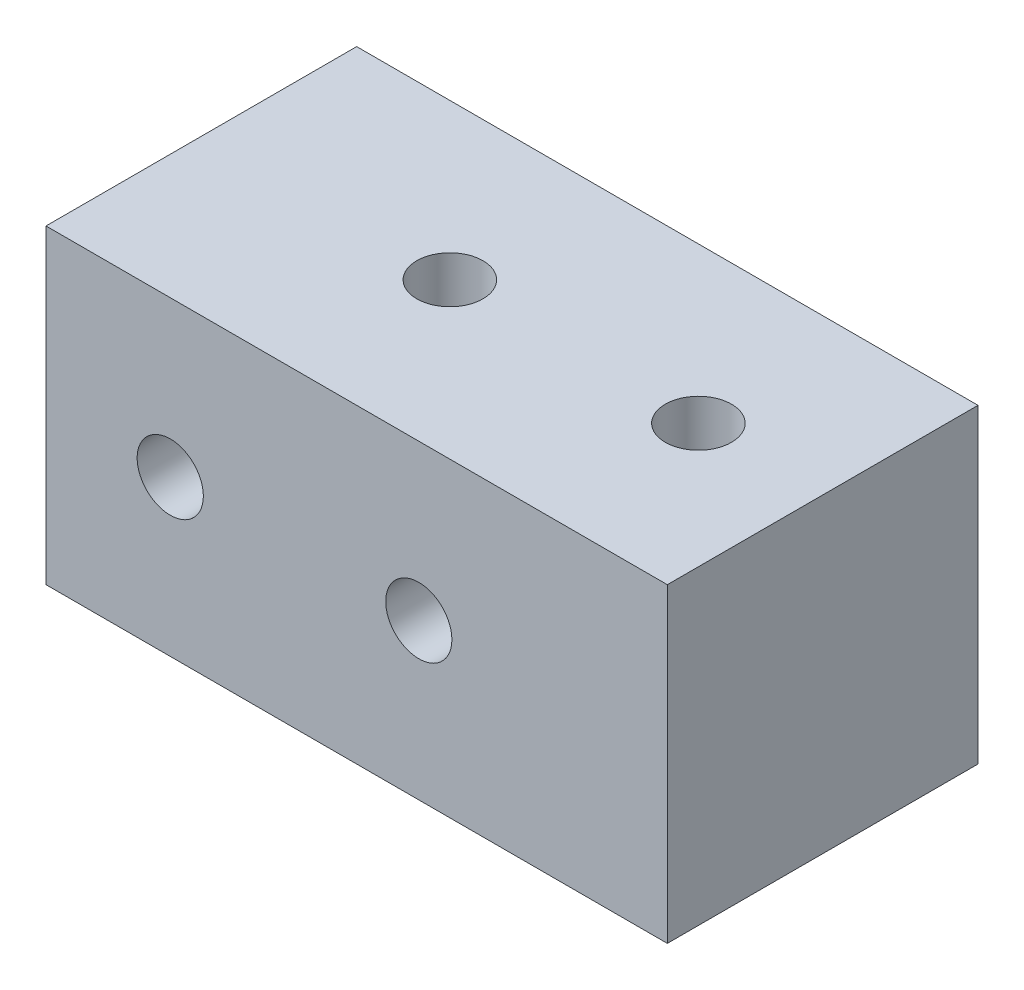
SolidWorks part; units mm, degrees
ref_plane "Front Plane" through (0, 0, 0) normal (0, 0, 1) x (1, 0, 0)
ref_plane "Top Plane" through (0, 0, 0) normal (0, 1, 0) x (1, 0, 0)
ref_plane "Right Plane" through (0, 0, 0) normal (1, 0, 0) x (0, 0, -1)
sketch "Sketch1" plane through (0, 0, 0) normal (0, 0, 1) x (1, 0, 0)
  line L1 (12.7, -6.35) -> (-12.7, -6.35)
  line L2 (12.7, -6.35) -> (12.7, 6.35)
  line L3 (12.7, 6.35) -> (-12.7, 6.35)
  line L4 (-12.7, -6.35) -> (-12.7, 6.35)
  line L5 (12.7, -6.35) -> (-12.7, 6.35) construction
  line L6 (12.7, 6.35) -> (-12.7, -6.35) construction
  point P0 (0, 0)
  dimension "D1" = 25.4
  dimension "D2" = 12.7
extrude "Boss-Extrude1" add sketch "Sketch1" along normal blind 12.7
hole_wizard "Tap Drill for #6-32 Tap1" positions "Sketch2" profile "Sketch3" hole size "#6-32" standard "ANSI Inch" end condition through all
sketch "Sketch2" plane through (0, 6.35, 0) normal (0, 1, 0) x (1, 0, 0)
  line L0 (-2.54, -6.35) -> (7.62, -6.35)
  line L2 (12.7, 0) -> (-12.7, 0) construction
  line L3 (2.54, -6.35) -> (2.54, 0)
  line L6 (12.7, -12.7) -> (12.7, 0) construction
  point P0 (-2.54, -6.35)
  point P2 (7.62, -6.35)
  dimension "D1" = 6.35
  dimension "D2" = 5.08
  dimension "D3" = 10.16
sketch "Sketch3" plane through (-2.54, 6.35, 6.35) normal (1, 0, 0) x (0, 0, 1)
  line L0 (0, 0) -> (0, 12.7)
  line L1 (0, 12.7) -> (1.3525, 12.7)
  line L2 (1.3525, 12.7) -> (1.3525, 0)
  line L5 (1.3525, 0) -> (0, 0)
  line L11 (0, -6.35) -> (0, 107.95) construction
  dimension "Thru Hole Dia." = 2.7051
  dimension "Thru Hole Depth" = 12.7
hole_wizard "Tap Drill for #6-32 Tap2" positions "Sketch4" profile "Sketch5" hole size "#6-32" standard "ANSI Inch" end condition through all
sketch "Sketch4" plane through (0, 0, 12.7) normal (0, 0, 1) x (1, 0, 0)
  line L0 (-7.62, 0) -> (2.54, 0)
  line L3 (12.7, 6.35) -> (-12.7, 6.35) construction
  line L4 (-12.7, 6.35) -> (-12.7, -6.35) construction
  point P0 (-7.62, 0)
  point P2 (2.54, 0)
  dimension "D1" = 5.08
  dimension "D2" = 10.16
  dimension "D3" = 6.35
sketch "Sketch5" plane through (-7.62, 0, 12.7) normal (1, 0, 0) x (0, -1, 0)
  line L0 (0, 0) -> (0, 12.7)
  line L1 (0, 12.7) -> (1.3525, 12.7)
  line L2 (1.3525, 12.7) -> (1.3525, 0)
  line L5 (1.3525, 0) -> (0, 0)
  line L11 (0, -6.35) -> (0, 107.95) construction
  dimension "Thru Hole Dia." = 2.7051
  dimension "Thru Hole Depth" = 12.7
